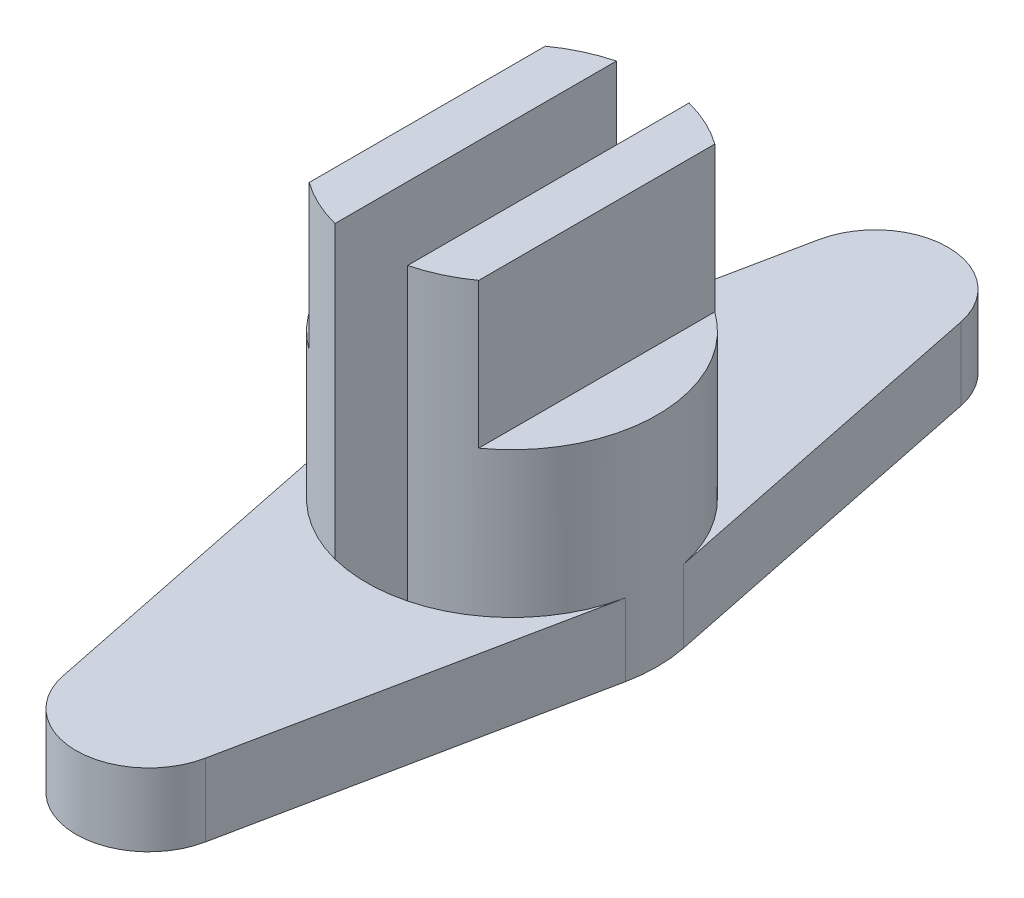
SolidWorks part; units mm, degrees
ref_plane "Front Plane" through (0, 0, 0) normal (0, 0, 1) x (1, 0, 0)
ref_plane "Top Plane" through (0, 0, 0) normal (0, 1, 0) x (1, 0, 0)
ref_plane "Right Plane" through (0, 0, 0) normal (1, 0, 0) x (0, 0, -1)
sketch "Sketch1" plane through (0, 0, 0) normal (0, 1, 0) x (1, 0, 0)
  line L0 (0, 0) -> (170.7075, 0) construction
  line L1 (-14.6969, 78) -> (-29.3939, 6)
  line L2 (0, -99) -> (0, 99) construction
  line L3 (14.6969, 78) -> (29.3939, 6)
  line L4 (14.6969, -78) -> (29.3939, -6)
  line L5 (-14.6969, -78) -> (-29.3939, -6)
  arc A0 (14.6969, 78) -> (-14.6969, 78) centre (0, 75) ccw
  arc A1 (-14.6969, -78) -> (14.6969, -78) centre (0, -75) ccw
  arc A2 (-29.3939, 6) -> (-29.3939, -6) centre (0, 0) ccw
  arc A3 (29.3939, -6) -> (29.3939, 6) centre (0, 0) ccw
  point P1 (-323.5431, 57.8142)
  dimension "D1" = 30
  dimension "D4" = 60
  dimension "D3" = 75
extrude "Boss-Extrude1" add sketch "Sketch1" along normal blind 15
sketch "Sketch2" plane through (0, 15, 0) normal (0, 1, 0) x (1, 0, 0)
  circle A0 centre (0, 0) radius 30
  arc A1 (29.3939, -6) -> (29.3939, 6) centre (0, 0) ccw construction
extrude "Boss-Extrude2" add sketch "Sketch2" along normal blind 60
sketch "Sketch3" plane through (0, 75, 0) normal (0, 1, 0) x (1, 0, 0)
  line L0 (0, 0) -> (0, 46.3598) construction
  line L2 (-7.5, 29.0474) -> (-7.5, -29.0474)
  line L4 (7.5, 29.0474) -> (7.5, -29.0474)
  circle A0 centre (0, 0) radius 30 construction
  arc A1 (-7.5, -29.0474) -> (7.5, -29.0474) centre (0, 0) ccw
  arc A2 (7.5, 29.0474) -> (-7.5, 29.0474) centre (0, 0) ccw
  dimension "D1" = 15
extrude "Cut-Extrude1" cut sketch "Sketch3" against normal through all
sketch "Sketch4" plane through (0, 75, 0) normal (0, 1, 0) x (1, 0, 0)
  line L4 (-17.5, 24.367) -> (-17.5, -24.367)
  line L5 (17.5, -24.367) -> (17.5, 24.367)
  line L6 (-7.5, 29.0474) -> (-7.5, -29.0474) construction
  line L7 (7.5, -29.0474) -> (7.5, 29.0474) construction
  arc A0 (7.5, -29.0474) -> (7.5, 29.0474) centre (0, 0) ccw construction
  arc A1 (-7.5, 29.0474) -> (-7.5, -29.0474) centre (0, 0) ccw construction
  arc A2 (17.5, -24.367) -> (17.5, 24.367) centre (0, 0) ccw
  arc A3 (-17.5, 24.367) -> (-17.5, -24.367) centre (0, 0) ccw
  dimension "D1" = 10
  dimension "D2" = 10
extrude "Cut-Extrude2" cut sketch "Sketch4" against normal blind 30
